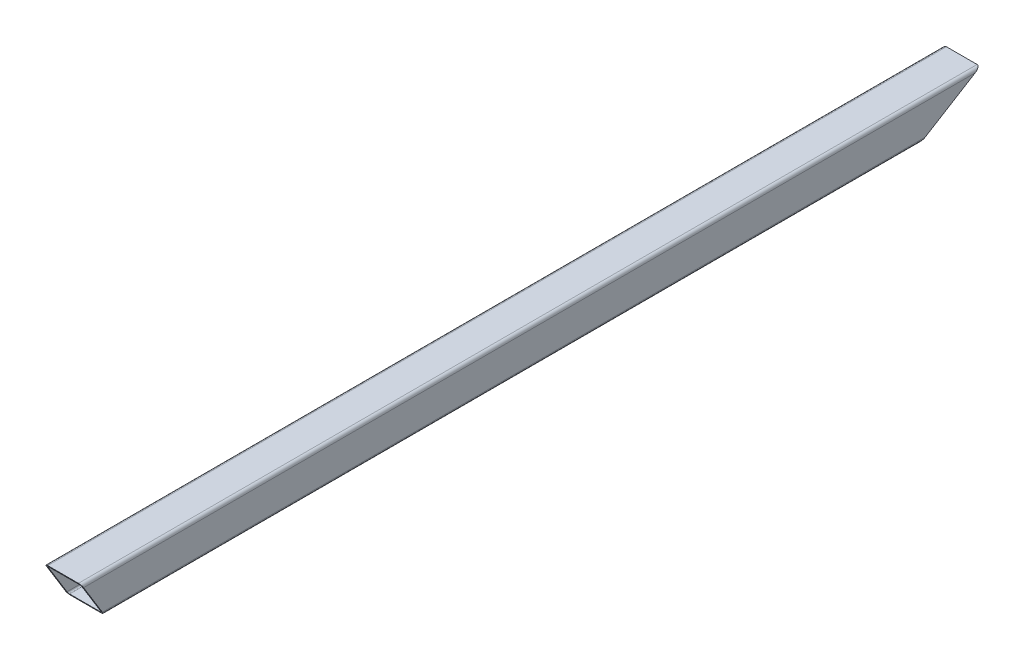
SolidWorks part; units mm, degrees
material "ASTM A36 Steel"
ref_plane "Front Plane" through (0, 0, 0) normal (0, 0, 1) x (1, 0, 0)
ref_plane "Top Plane" through (0, 0, 0) normal (0, 1, 0) x (1, 0, 0)
ref_plane "Right Plane" through (0, 0, 0) normal (1, 0, 0) x (0, 0, -1)
sketch "Sketch1" plane through (0, 0, 0) normal (0, 0, 1) x (1, 0, 0)
  line L1 (22.6308, 17.3538) -> (-35.3692, 17.3538)
  line L2 (25.6308, 14.3538) -> (25.6308, -43.6462)
  line L3 (22.6308, -46.6462) -> (-35.3692, -46.6462)
  line L4 (-38.3692, 14.3538) -> (-38.3692, -43.6462)
  line L5 (22.6308, 20.3538) -> (-35.3692, 20.3538)
  line L6 (28.6308, 14.3538) -> (28.6308, -43.6462)
  line L7 (22.6308, -49.6462) -> (-35.3692, -49.6462)
  line L8 (-41.3692, 14.3538) -> (-41.3692, -43.6462)
  arc A0 (28.6308, -43.6462) -> (22.6308, -49.6462) centre (22.6308, -43.6462) cw
  arc A1 (-35.3692, -49.6462) -> (-41.3692, -43.6462) centre (-35.3692, -43.6462) cw
  arc A2 (-41.3692, 14.3538) -> (-35.3692, 20.3538) centre (-35.3692, 14.3538) cw
  arc A3 (28.6308, 14.3538) -> (22.6308, 20.3538) centre (22.6308, 14.3538) ccw
  arc A4 (22.6308, -46.6462) -> (25.6308, -43.6462) centre (22.6308, -43.6462) ccw
  arc A5 (-35.3692, -46.6462) -> (-38.3692, -43.6462) centre (-35.3692, -43.6462) cw
  arc A6 (-38.3692, 14.3538) -> (-35.3692, 17.3538) centre (-35.3692, 14.3538) cw
  arc A7 (25.6308, 14.3538) -> (22.6308, 17.3538) centre (22.6308, 14.3538) ccw
  point P12 (-41.3692, -49.6462)
  point P15 (-41.3692, 20.3538)
  point P18 (28.6308, 20.3538)
  point P23 (-38.3692, -46.6462)
  point P26 (-38.3692, 17.3538)
  point P29 (25.6308, 17.3538)
  dimension "D7" = 6
  dimension "D8" = 3
  dimension "D1" = 70
  dimension "D2" = 70
  dimension "D3" = 3
  dimension "D4" = 3
  dimension "D5" = 64
  dimension "D6" = 64
extrude "Boss-Extrude1" add sketch "Sketch1" along normal blind 1700
sketch "Sketch2" plane through (28.6308, 0, 0) normal (1, 0, 0) x (0, 0, -1)
  line L0 (0, 20.3538) -> (-114, -49.6462)
  line L1 (-1700, -49.6462) -> (0, -49.6462) construction
  line L2 (-114, -49.6462) -> (0, -49.6462)
  line L3 (0, -49.6462) -> (0, 20.3538)
  line L4 (-1700, 20.3538) -> (-1657, -49.6462)
  line L5 (-1657, -49.6462) -> (-1700, -49.6462)
  line L6 (-1700, -49.6462) -> (-1700, 20.3538)
  dimension "D1" = 114
  dimension "D2" = 70
  dimension "D3" = 43
extrude "Cut-Extrude1" cut sketch "Sketch2" against normal blind 1170
